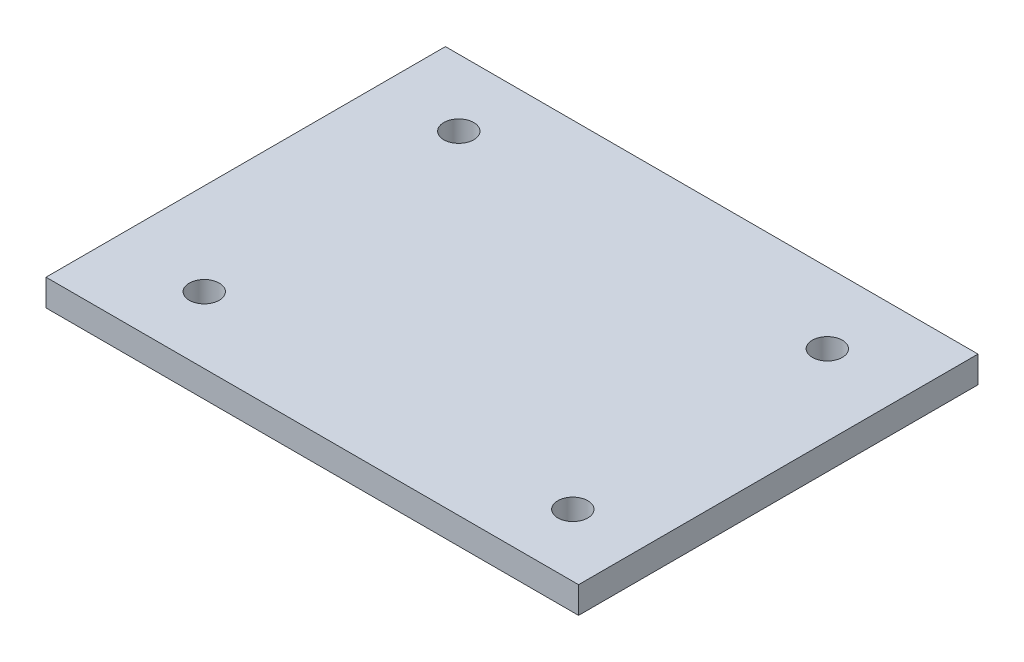
SolidWorks part; units mm, degrees
ref_plane "Front Plane" through (0, 0, 0) normal (0, 0, 1) x (1, 0, 0)
ref_plane "Top Plane" through (0, 0, 0) normal (0, 1, 0) x (1, 0, 0)
ref_plane "Right Plane" through (0, 0, 0) normal (1, 0, 0) x (0, 0, -1)
sketch "Sketch1" plane through (0, 0, 0) normal (0, 1, 0) x (1, 0, 0)
  line L1 (0, 0) -> (80, 0)
  line L2 (0, 0) -> (0, -60)
  line L3 (0, -60) -> (80, -60)
  line L4 (80, 0) -> (80, -60)
  dimension "D1" = 80
  dimension "D2" = 60
extrude "Boss-Extrude1" add sketch "Sketch1" along normal blind 4
sketch "Sketch2" plane through (0, 4, 0) normal (0, 1, 0) x (1, 0, 0)
  line L0 (80, -60) -> (80, 0) construction
  line L1 (80, 0) -> (0, 0) construction
  circle A0 centre (12.0036, -10) radius 2.25
  circle A1 centre (68, -10.6325) radius 2.25
  circle A2 centre (69.7673, -50.6325) radius 2.25
  circle A3 centre (13.7708, -50) radius 2.25
  dimension "D1" = 4.5
  dimension "D2" = 4.5
  dimension "D3" = 4.5
  dimension "D4" = 4.5
  dimension "D5" = 56
  dimension "D6" = 56
  dimension "D7" = 40
  dimension "D8" = 12
  dimension "D9" = 10
  dimension "D10" = 40
extrude "Cut-Extrude1" cut sketch "Sketch2" against normal through all
